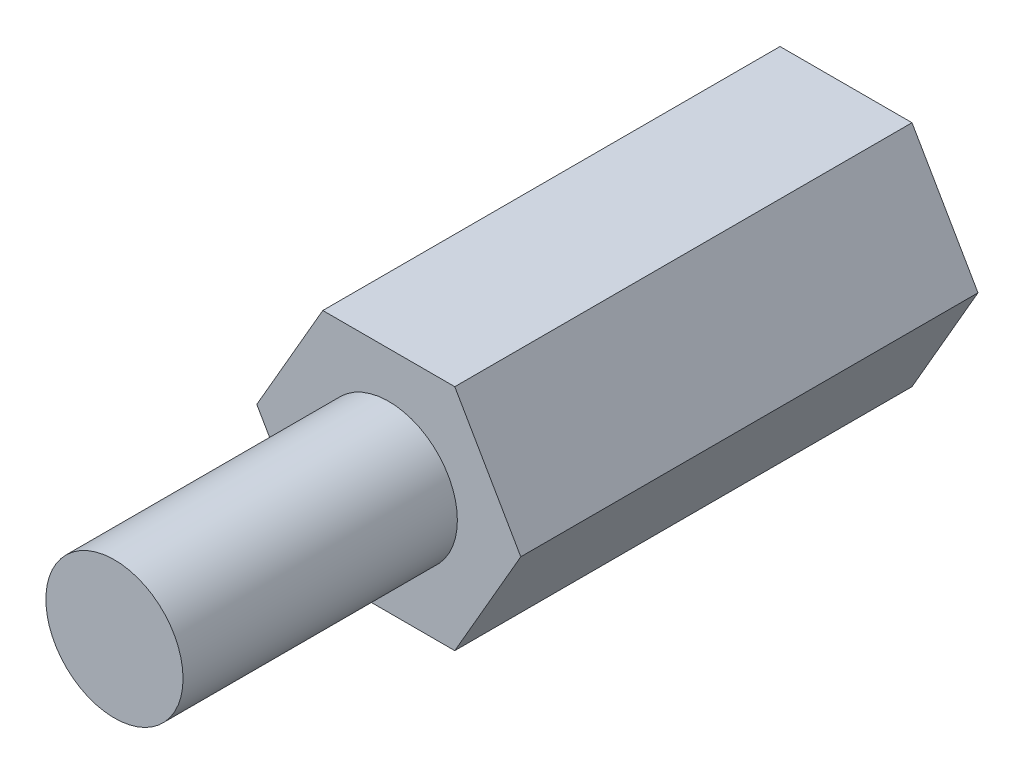
SolidWorks part; units mm, degrees
ref_plane "前视基准面" through (0, 0, 0) normal (0, 0, 1) x (1, 0, 0)
ref_plane "上视基准面" through (0, 0, 0) normal (0, 1, 0) x (1, 0, 0)
ref_plane "右视基准面" through (0, 0, 0) normal (1, 0, 0) x (0, 0, -1)
sketch "草图1" plane through (0, 0, 0) normal (0, 0, 1) x (1, 0, 0)
  line L0 (-28.6627, 0) -> (33.6774, 0) construction
  line L1 (1.4434, -2.5) -> (2.8868, 0)
  line L2 (2.8868, 0) -> (1.4434, 2.5)
  line L3 (1.4434, 2.5) -> (-1.4434, 2.5)
  line L4 (-1.4434, 2.5) -> (-2.8868, 0)
  line L5 (-2.8868, 0) -> (-1.4434, -2.5)
  line L6 (-1.4434, -2.5) -> (1.4434, -2.5)
  circle A0 centre (0, 0) radius 2.5 construction
  dimension "D1" = 5
extrude "拉伸1" add sketch "草图1" along normal blind 10
sketch "草图2" plane through (0, 0, 10) normal (0, 0, 1) x (1, 0, 0)
  circle A0 centre (0, 0) radius 1.5
  dimension "D1" = 3
extrude "拉伸2" add sketch "草图2" along normal blind 6
hole_wizard "M3x0.5 螺纹孔1" positions "3D草图2" profile "草图5" tap size "M3x0.5" standard "ISO"
sketch3d "3D草图2"
  point P0 (0, 0, 0)
  point P2 (0, 0, 0)
  point P3 (0, 0, 0)
  point P4 (0, 0, 0)
cosmetic thread "孔螺蚊线1" parameters "D1"=4, "D2"=3
sketch "草图5" plane through (0, 0, 0) normal (1, 0, 0) x (0, 1, 0)
  line L0 (0, 0) -> (0, 7.2511)
  line L1 (0, 7.2511) -> (1.25, 6.5)
  line L2 (1.25, 6.5) -> (1.25, 0)
  line L5 (1.25, 0) -> (0, 0)
  line L10 (0, 7.2511) -> (-1.25, 6.5) construction
  line L11 (0, -6.35) -> (0, 107.95) construction
  dimension "蹟恇謂郰芛眻噤" = 2.5
  dimension "蹟恇謂郰芛旮僅" = 6.5
  dimension "絳芛褒僅" = 118
cosmetic thread "孔螺蚊线2" parameters "D1"=4, "D2"=3
cosmetic thread "孔螺蚊线3" parameters "D1"=4, "D2"=3
cosmetic thread "孔螺蚊线4" parameters "D1"=4, "D2"=3
sketch "草图6" plane through (0, 0, 0) normal (0, 0, -1) x (-1, 0, 0)
  circle A0 centre (0, 0) radius 1.5
  dimension "D1" = 3
extrude "拉伸3" [suppressed] add sketch "草图6" along normal blind 10
